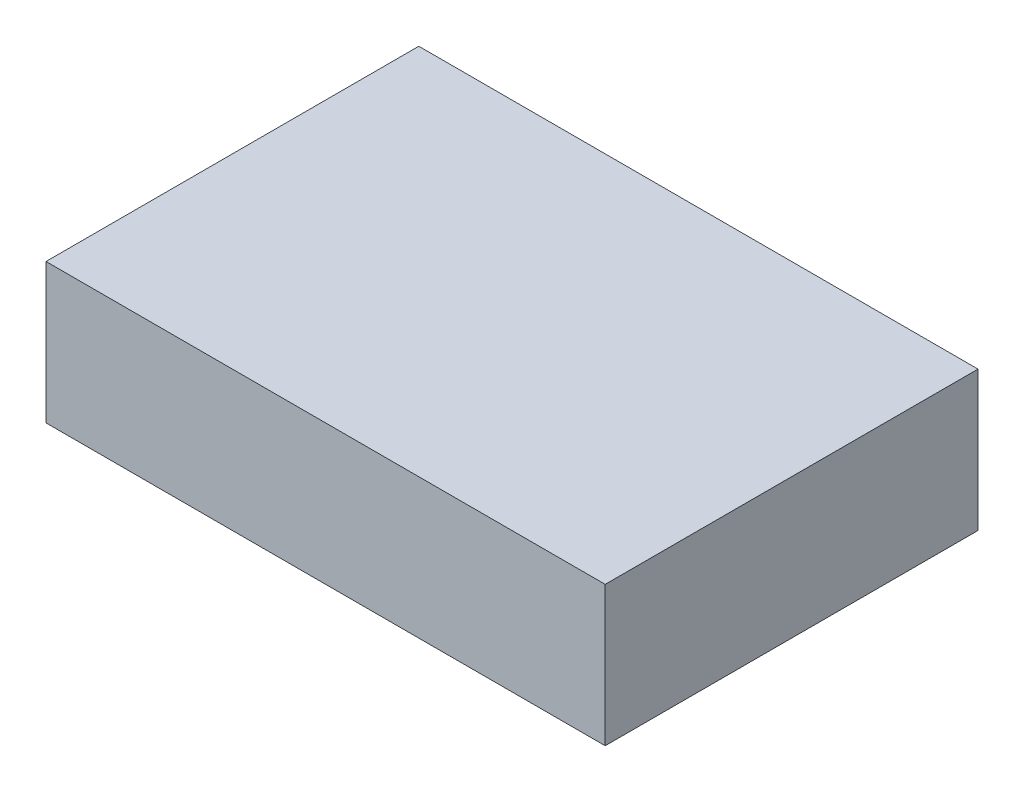
SolidWorks part; units mm, degrees
material "ABS"
ref_plane "Front Plane" through (0, 0, 0) normal (0, 0, 1) x (1, 0, 0)
ref_plane "Top Plane" through (0, 0, 0) normal (0, 1, 0) x (1, 0, 0)
ref_plane "Right Plane" through (0, 0, 0) normal (1, 0, 0) x (0, 0, -1)
sketch "Sketch1" plane through (0, 0, 0) normal (0, 0, 1) x (1, 0, 0)
  line L1 (-45.1303, 23.1413) -> (74.8697, 23.1413)
  line L2 (-45.1303, 23.1413) -> (-45.1303, -6.8587)
  line L3 (-45.1303, -6.8587) -> (74.8697, -6.8587)
  line L4 (74.8697, 23.1413) -> (74.8697, -6.8587)
  dimension "D1" = 120
  dimension "D2" = 30
extrude "Boss-Extrude1" add sketch "Sketch1" along normal blind 80
shell "Shell1" thickness 5
sketch "Sketch2" plane through (0, 0, 0) normal (0, 0, -1) x (-1, 0, 0)
  line L0 (45.1303, -6.8587) -> (-74.8697, -6.8587) construction
  line L1 (45.1303, 23.1413) -> (45.1303, -6.8587) construction
  circle A0 centre (30.1303, 7.8145) radius 4.1759
  dimension "D1" = 14.6732
  dimension "D2" = 15
extrude "Cut-Extrude1" cut sketch "Sketch2" against normal blind 15
pattern_linear "LPattern1" count 4 spacing 110 along (-1, 0, 0) of "Cut-Extrude1"
